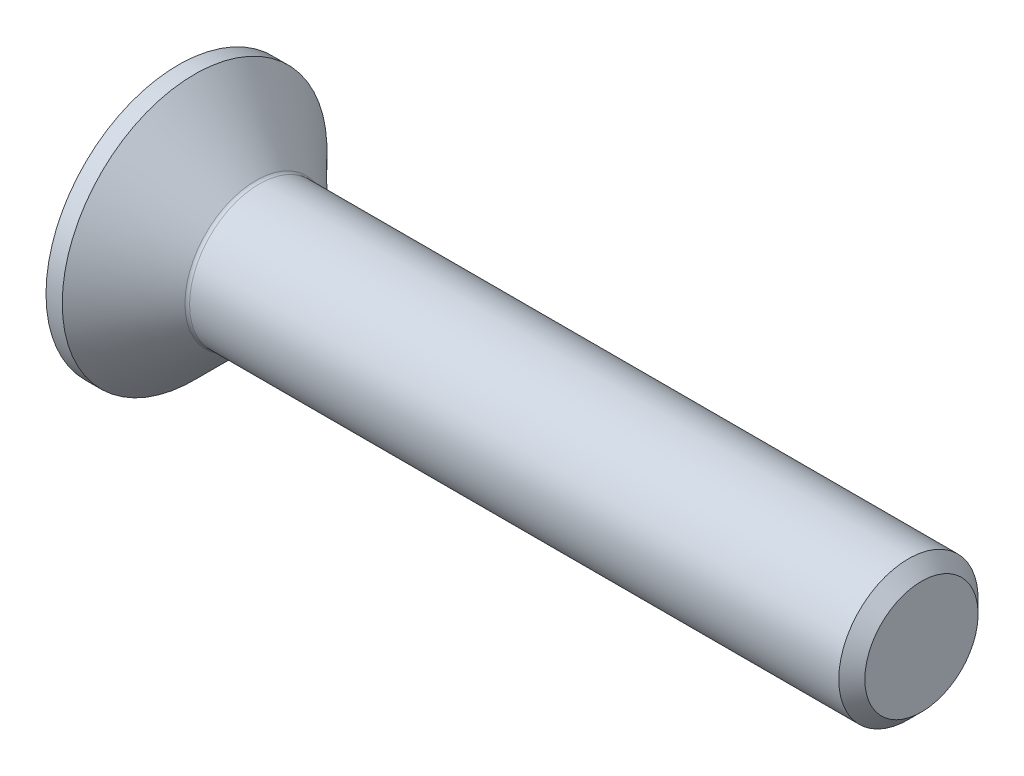
SolidWorks part; units mm, degrees
ref_plane "Plane1" through (0, 0, 0) normal (0, 0, 1) x (1, 0, 0)
ref_plane "Plane2" through (0, 0, 0) normal (0, 1, 0) x (1, 0, 0)
ref_plane "Plane3" through (0, 0, 0) normal (1, 0, 0) x (0, 0, -1)
sketch "BodySke" plane through (0, 0, 0) normal (0, 0, 1) x (1, 0, 0)
  line L0 (0, 0) -> (0, 2.85)
  line L1 (0.35, 2.85) -> (1.7, 1.5)
  line L2 (0, 2.85) -> (0.35, 2.85)
  line L3 (1.7, 1.5) -> (15.7195, 1.5)
  line L4 (16, 1.2195) -> (16, 0)
  line L5 (16, 0) -> (0, 0)
  line L6 (0, 0) -> (127, 0) construction
  line L7 (0.35, -2.85) -> (1.7, -1.5) construction
  line L8 (16, 1.2195) -> (15.7195, 1.5)
  line L9 (0, -2.85) -> (0.35, -2.85) construction
  line L10 (16, -1.2195) -> (15.7195, -1.5) construction
  line L11 (2.2, 7.85) -> (2.2, -14.375) construction
  line L12 (0, 16.35) -> (0, -5.875) construction
  dimension "Diameter" = 3
  dimension "Head_ht" = 1.7
  dimension "Length" = 16
  dimension "Body_ch_ang" = 45
  dimension "Head_dia" = 5.7
  dimension "Minor_dia" = 2.439
  dimension "Head_ang" = 90
  dimension "Advance" = 0.5
  dimension "Thread_nom" = 16
revolve "BaseBody" add sketch "BodySke" angle 360 about L6
cosmetic thread "ThreadCosmetic" [suppressed] parameters "Thread_length"=13.55, "Thread_minor"=2.439
fillet "Fillet1" radius 0.1 1 edges at (1.7, 0, 1.5)
sketch "Sketch2" plane through (0, 0, 0) normal (0, 0, 1) x (1, 0, 0)
  line L0 (0, 1.01) -> (1.2, 1.01)
  line L1 (1.2, 1.01) -> (1.7831, 0)
  line L2 (0, 0) -> (127, 0) construction
  line L3 (1.7831, 0) -> (0, 0)
  line L4 (0, 0) -> (0, 1.01)
  line L5 (0, -1.01) -> (1.2, -1.01) construction
  line L6 (0, 0) -> (47.625, 0) construction
  line L8 (0, 2.85) -> (0, -2.85) construction
  dimension "D2" = 60
  dimension "PreBroach_depth" = 1.2
  dimension "PreBroach_dia" = 2.02
revolve "PreBroach" cut sketch "Sketch2" angle 360 about L6
sketch "Sketch3" plane through (0, 0, 0) normal (-1, 0, 0) x (0, 0, 1)
  line L0 (-1.01, -0.5831) -> (-1.01, 0.5831)
  line L1 (-1.01, 0.5831) -> (0, 1.1662)
  line L2 (0, 1.1662) -> (1.01, 0.5831)
  line L3 (1.01, 0.5831) -> (1.01, -0.5831)
  line L4 (1.01, -0.5831) -> (0, -1.1662)
  line L5 (0, -1.1662) -> (-1.01, -0.5831)
  dimension "D1" = 1.01
  dimension "D2" = 1.01
  dimension "D3" = 2.02
  dimension "Hex_size" = 2.02
extrude "Hex" cut sketch "Sketch3" against normal blind 1.2
sketch "ThdSchSke" plane through (0, 0, 0) normal (0, 0, 1) x (1, 0, 0)
  line L0 (2.45, -1.2195) -> (2.2536, -1.5)
  line L1 (2.45, -1.2195) -> (2.6464, -1.5)
  line L2 (2.6464, -1.5) -> (2.6464, -1.875)
  line L3 (-3.175, 0) -> (5.1513, 0) construction
  line L4 (0, 2.85) -> (0, -2.85) construction
  line L5 (2.6464, -1.875) -> (2.2536, -1.875)
  line L6 (2.2536, -1.875) -> (2.2536, -1.5)
  dimension "Thread_minor" = 2.439
  dimension "Diameter" = 3
  dimension "Start" = 2.45
  dimension "SideAngle" = 55
  dimension "VeeAngle" = 70
  dimension "Overcut" = 3.75
revolve "ThreadSchematic" [suppressed] cut sketch "ThdSchSke" angle 360 about L3
pattern_linear "ThdSchPat" [suppressed]
equation "\"Thread_minor@ThreadCosmetic\"  =  \"Minor_dia@BodySke\""
equation "\"D1@Sketch3\" = \"Hex_size@Sketch3\" / 2"
equation "\"D2@Sketch3\" = \"D1@Sketch3\""
equation "\"D3@Sketch3\" = \"Hex_size@Sketch3\""
equation "\"Thread_length@ThreadCosmetic\" = ((sgn( (\"Length@BodySke\" - \"Advance@BodySke\" * 1.5 - \"Head_ht@BodySke\" ) - \"Thread_nom@BodySke\" )-1)*( (\"Length@BodySke\" - \"Advance@BodySke\" * 1.5 - \"Head_ht@BodySke\" ) - \"Thread_nom@BodySke\" ))/-2+ \"Thread_nom@BodySke\""
equation "\"Thread_minor@ThdSchSke\" = \"Minor_dia@BodySke\""
equation "\"Diameter@ThdSchSke\" = \"Diameter@BodySke\""
equation "\"Overcut@ThdSchSke\" = \"Diameter@BodySke\" * 1.25"
equation "\"Start@ThdSchSke\" = 0.000001 + \"Length@BodySke\" - \"Thread_length@ThreadCosmetic\"  '---Countersunk---"
equation "\"Num_threads@ThdSchPat\" = int( \"Thread_length@ThreadCosmetic\" / \"Advance@BodySke\" + 0.999 )  + 1"
equation "\"Advance@ThdSchPat\" = \"Thread_length@ThreadCosmetic\" /  (\"Num_threads@ThdSchPat\" - 1) 'relax it"
equation "\"Num_threads@ThdSchPat\" = \"Num_threads@ThdSchPat\" - sgn( \"Num_threads@ThdSchPat\" - 1) '---chamfered tips only---"
